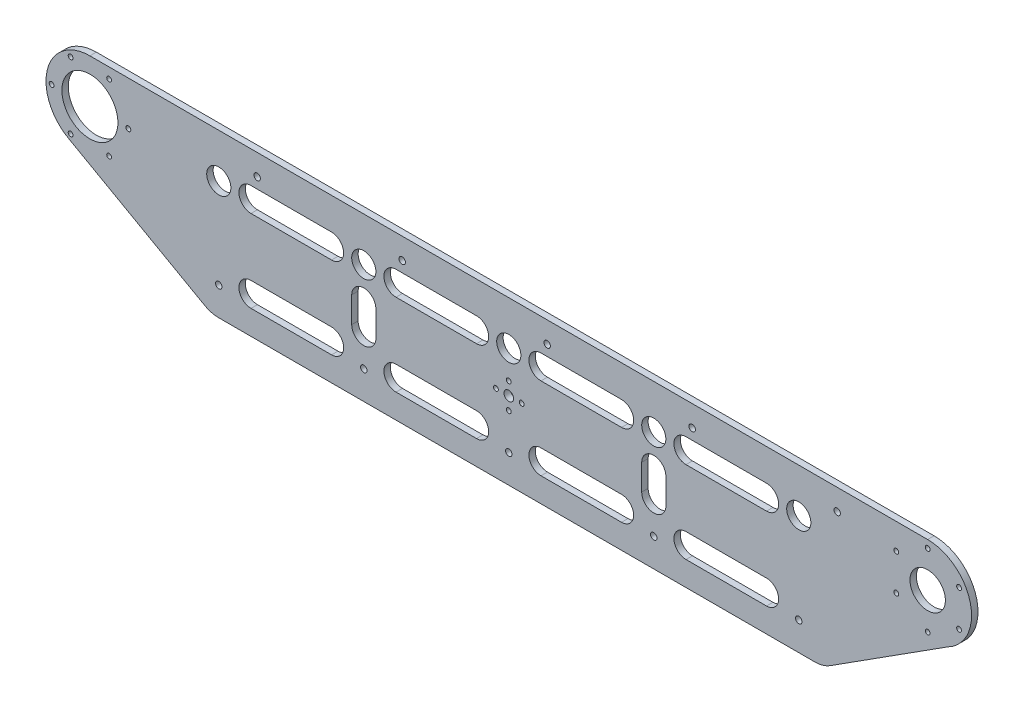
SolidWorks part; units mm, degrees
ref_plane "Alzado" through (0, 0, 0) normal (0, 0, 1) x (1, 0, 0)
ref_plane "Planta" through (0, 0, 0) normal (0, 1, 0) x (1, 0, 0)
ref_plane "Vista lateral" through (0, 0, 0) normal (1, 0, 0) x (0, 0, -1)
sketch "Croquis2" plane through (0, 0, 0) normal (0, 0, 1) x (1, 0, 0)
  line L0 (102.5, 23.182) -> (90, 21.1607) construction
  line L1 (90, -23.8925) -> (180, -23.8925) construction
  line L2 (-102.5, -9.9669) -> (-83.0991, -6.8298) construction
  line L3 (-215.9366, -23.8925) -> (-260, -23.8925) construction
  line L4 (-90, -23.8925) -> (-92, -23.8925) construction
  line L5 (-188.6184, -23.8925) -> (-182, -23.8925) construction
  line L6 (-260, -23.8925) -> (-260, 1.2874) construction
  line L7 (-179.1956, -41.4802) -> (179.1956, -41.4802)
  line L8 (-260, 32.1075) -> (-180, -23.8925) construction
  line L9 (179.1956, -41.4802) -> (190.0108, -41.4802)
  line L10 (0, -23.8925) -> (-12.5, -23.8925) construction
  line L11 (-180, -23.8925) -> (-167.5, -23.8925) construction
  line L12 (-90, -23.8925) -> (-92, -23.8925) construction
  line L13 (-90, -23.8925) -> (-90, 32.1075) construction
  line L14 (-182, -23.9062) -> (-188.6184, -23.8925) construction
  line L15 (-180, -23.8925) -> (-196.3846, -12.4232) construction
  line L16 (-196.3846, -12.4232) -> (-221.6689, 5.2758) construction
  line L17 (-260, 32.1075) -> (-243.6154, 20.6383) construction
  line L18 (-272.7427, 8.0318) -> (-188.6256, -39.2409)
  line L19 (-90, 32.1075) -> (-90, 12.1075) construction
  line L20 (-90, -23.8925) -> (-90, -3.8925) construction
  line L21 (-82.5, 12.1075) -> (-82.5, -3.8925)
  line L22 (-97.5, 12.1075) -> (-97.5, -3.8925)
  line L23 (-90, 44.6075) -> (-90, -11.3925) construction
  line L24 (-20, 24.6075) -> (-70, 24.6075)
  line L25 (-20, 39.6075) -> (-70, 39.6075)
  line L26 (287.24, 32.1075) -> (284.0739, 32.1075) construction
  line L27 (260, 59.3475) -> (260, 32.1075) construction
  line L28 (90, 44.6075) -> (90, -11.3925) construction
  line L29 (90, -23.8925) -> (90, -3.8925) construction
  line L30 (90, 32.1075) -> (90, 12.1075) construction
  line L31 (260, 32.1075) -> (260, 39.1075) construction
  line L32 (160, -26.3925) -> (110, -26.3925)
  line L33 (-260, 4.1) -> (-260, 32.1075) construction
  line L34 (160, -11.3925) -> (110, -11.3925)
  line L35 (20, -11.3925) -> (70, -11.3925)
  line L36 (20, 39.6075) -> (70, 39.6075)
  line L37 (260, 32.1075) -> (260, 25.1075) construction
  line L38 (-160, 39.6075) -> (-110, 39.6075)
  line L39 (-160, 24.6075) -> (-110, 24.6075)
  line L40 (20, -26.3925) -> (70, -26.3925)
  line L41 (-260, 59.3475) -> (260, 59.3475)
  line L42 (-287.24, 32.1075) -> (-284.0739, 32.1075) construction
  line L43 (-20, -26.3925) -> (-70, -26.3925)
  line L44 (160, 24.6075) -> (110, 24.6075)
  line L45 (-20, -11.3925) -> (-70, -11.3925)
  line L46 (-167.5, -23.8925) -> (-180, -23.8925) construction
  line L47 (-102.5, 23.182) -> (-90, 21.1607) construction
  line L48 (160, 39.6075) -> (110, 39.6075)
  line L49 (-6.5, 6.6075) -> (-141.7981, 6.6075) construction
  line L50 (90, -23.8925) -> (88, -23.8925) construction
  line L51 (-135, 39.6075) -> (-135, 14.7545) construction
  line L52 (135, 39.6075) -> (135, 20.6383) construction
  line L53 (-88, -23.8925) -> (-90, -23.8925) construction
  line L54 (-160, -26.3925) -> (-110, -26.3925)
  line L55 (-83.0991, -6.8298) -> (-102.5, -9.9669) construction
  line L56 (-90, 21.1607) -> (-102.5, 23.182) construction
  line L57 (-160, -11.3925) -> (-110, -11.3925)
  line L58 (83.0991, -6.8298) -> (102.5, -9.9669) construction
  line L59 (90, 21.1607) -> (102.5, 23.182) construction
  line L60 (90, -23.8925) -> (90, 32.1075) construction
  line L61 (90, -23.8925) -> (92, -23.8925) construction
  line L62 (265.4417, 3.373) -> (265.4184, 3.7892) construction
  line L63 (90, -23.8925) -> (92, -23.8925) construction
  line L64 (102.5, -9.9669) -> (83.0991, -6.8298) construction
  line L65 (20, 24.6075) -> (70, 24.6075)
  line L66 (97.5, 12.1075) -> (97.5, -3.8925)
  line L67 (82.5, 12.1075) -> (82.5, -3.8925)
  line L68 (272.7427, 8.0318) -> (199.4836, -38.7153)
  circle A0 centre (0, -23.8925) radius 2
  circle A1 centre (-90, -23.8925) radius 2
  circle A2 centre (-180, -23.8925) radius 2
  circle A3 centre (-90, 32.1075) radius 7.5
  arc A4 (-82.5, 12.1075) -> (-97.5, 12.1075) centre (-90, 12.1075) ccw
  arc A5 (-97.5, -3.8925) -> (-82.5, -3.8925) centre (-90, -3.8925) ccw
  arc A6 (-20, 39.6075) -> (-20, 24.6075) centre (-20, 32.1075) cw
  arc A7 (-70, 24.6075) -> (-70, 39.6075) centre (-70, 32.1075) cw
  circle A8 centre (0, 32.1075) radius 7.5
  circle A9 centre (-260, 32.1075) radius 17.4
  arc A10 (-260, 59.3475) -> (-272.7427, 8.0318) centre (-260, 32.1075) ccw
  arc A11 (-188.6256, -39.2409) -> (-179.1956, -41.4802) centre (-180, -23.8925) ccw
  arc A12 (260, 59.3475) -> (272.7427, 8.0318) centre (260, 32.1075) cw
  circle A13 centre (260, 32.1075) radius 11
  arc A14 (70, 24.6075) -> (70, 39.6075) centre (70, 32.1075) ccw
  arc A15 (20, 39.6075) -> (20, 24.6075) centre (20, 32.1075) ccw
  arc A16 (97.5, -3.8925) -> (82.5, -3.8925) centre (90, -3.8925) cw
  arc A17 (82.5, 12.1075) -> (97.5, 12.1075) centre (90, 12.1075) cw
  circle A18 centre (90, 32.1075) radius 7.5
  circle A19 centre (90, -23.8925) radius 2
  arc A20 (-160, 39.6075) -> (-160, 24.6075) centre (-160, 32.1075) ccw
  arc A21 (-110, 24.6075) -> (-110, 39.6075) centre (-110, 32.1075) ccw
  arc A22 (160, 39.6075) -> (160, 24.6075) centre (160, 32.1075) cw
  arc A23 (110, 24.6075) -> (110, 39.6075) centre (110, 32.1075) cw
  circle A24 centre (-180, 32.1075) radius 7.5
  circle A25 centre (180, 32.1075) radius 7.5
  circle A26 centre (-8, 6.6075) radius 1.5
  circle A27 centre (0, 14.6075) radius 1.5
  circle A28 centre (8, 6.6075) radius 1.5
  circle A29 centre (0, -1.3925) radius 1.5
  circle A30 centre (0, 6.6075) radius 3
  circle A31 centre (180, -23.8925) radius 2
  arc A32 (199.4836, -38.7153) -> (190.0108, -41.4802) centre (190.0108, -23.8702) cw
  arc A33 (160, -26.3925) -> (160, -11.3925) centre (160, -18.8925) ccw
  arc A34 (110, -11.3925) -> (110, -26.3925) centre (110, -18.8925) ccw
  arc A35 (20, -26.3925) -> (20, -11.3925) centre (20, -18.8925) cw
  arc A36 (70, -11.3925) -> (70, -26.3925) centre (70, -18.8925) cw
  arc A37 (-20, -26.3925) -> (-20, -11.3925) centre (-20, -18.8925) ccw
  arc A38 (-70, -11.3925) -> (-70, -26.3925) centre (-70, -18.8925) ccw
  arc A39 (-110, -11.3925) -> (-110, -26.3925) centre (-110, -18.8925) cw
  arc A40 (-160, -26.3925) -> (-160, -11.3925) centre (-160, -18.8925) cw
  circle A41 centre (260, 9.6075) radius 1.5
  circle A42 centre (279.4856, 20.8575) radius 1.5
  circle A43 centre (279.4856, 43.3575) radius 1.5
  circle A44 centre (260, 54.6075) radius 1.5
  circle A45 centre (240.5144, 43.3575) radius 1.5
  circle A46 centre (240.5144, 20.8575) radius 1.5
  circle A47 centre (203.8344, 46.2175) radius 2
  circle A48 centre (113.8344, 46.2175) radius 2
  circle A49 centre (23.8344, 46.2175) radius 2
  circle A50 centre (-66.1656, 46.2175) radius 2
  circle A51 centre (-156.1656, 46.2175) radius 2
  circle A52 centre (-248.05, 11.4095) radius 1.5
  circle A53 centre (-236.1, 32.1075) radius 1.5
  circle A54 centre (-248.05, 52.8055) radius 1.5
  circle A55 centre (-271.95, 52.8055) radius 1.5
  circle A56 centre (-283.74, 32.1075) radius 1.5
  circle A57 centre (-271.95, 11.4095) radius 1.5
  point P0 (0, 6.6075)
  dimension "D2" = 4
  dimension "D4" = 4
  dimension "D6" = 4
  dimension "D11" = 15
  dimension "D14" = 15
  dimension "D16" = 15
  dimension "D17" = 15
  dimension "D18" = 34.8
  dimension "D19" = 54.48
  dimension "D20" = 22
  dimension "D24" = 3
  dimension "D25" = 6
  dimension "D26" = 4
  dimension "D28" = 4
  dimension "D29" = 17.61
  dimension "D1" = 30.5
  dimension "D3" = 90
  dimension "D5" = 90
  dimension "D7" = 80
  dimension "D8" = 56
  dimension "D9" = 20
  dimension "D10" = 20
  dimension "D12" = 20
  dimension "D13" = 56
  dimension "D15" = 20
  dimension "D21" = 27.24
  dimension "D22" = 7
  dimension "D23" = 7
  dimension "D27" = 90
extrude "Saliente-Extruir1" add sketch "Croquis2" along normal blind 4
